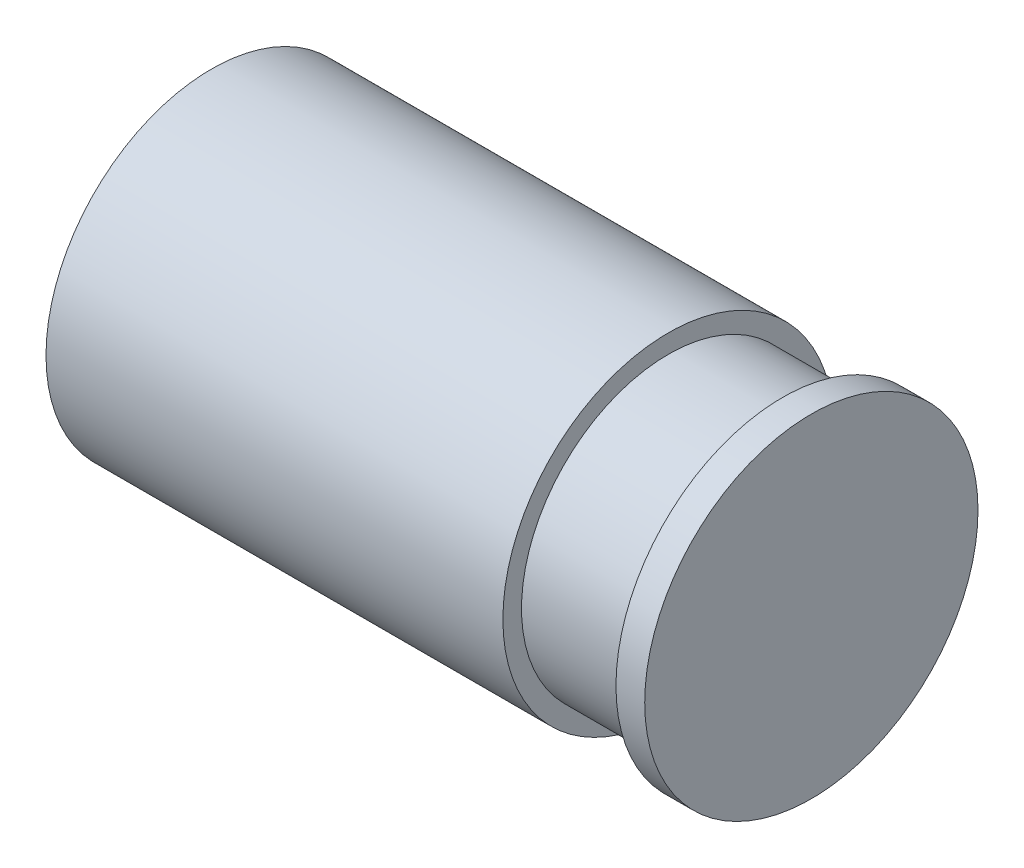
SolidWorks part; units mm, degrees
ref_plane "Front Plane" through (0, 0, 0) normal (0, 0, 1) x (1, 0, 0)
ref_plane "Top Plane" through (0, 0, 0) normal (0, 1, 0) x (1, 0, 0)
ref_plane "Right Plane" through (0, 0, 0) normal (1, 0, 0) x (0, 0, -1)
sketch "Sketch1" plane through (0, 0, 0) normal (0, 0, 1) x (1, 0, 0)
  line L0 (0, 0) -> (0, 24.8206)
  line L1 (0, 24.8206) -> (68.544, 24.8206)
  line L2 (68.544, 24.8206) -> (68.544, 22.0281)
  line L3 (68.544, 22.0281) -> (85.6845, 22.0281)
  line L4 (85.6845, 22.0281) -> (85.6845, 25)
  line L5 (85.6845, 25) -> (90, 25)
  line L6 (90, 25) -> (90, 0)
  line L7 (90, 0) -> (0, 0)
  line L8 (0, 0) -> (-9.0426, 0) construction
  line L9 (-9.0426, 0) -> (117.8661, 0) construction
  point P12 (0, 0)
  point P13 (100.2958, 0)
  point P14 (117.8661, 0)
  dimension "D1" = 25
  dimension "D2" = 90
revolve "Revolve1" add sketch "Sketch1" angle 360 about L8
